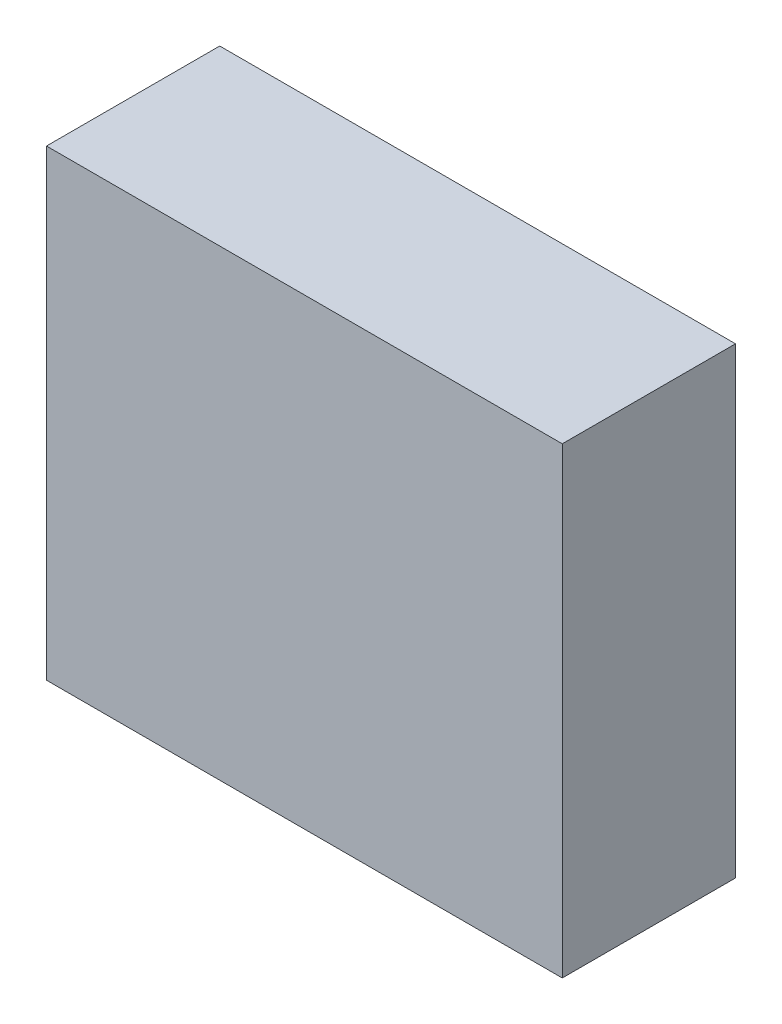
SolidWorks part; units mm, degrees
ref_plane "Front Plane" through (0, 0, 0) normal (0, 0, 1) x (1, 0, 0)
ref_plane "Top Plane" through (0, 0, 0) normal (0, 1, 0) x (1, 0, 0)
ref_plane "Right Plane" through (0, 0, 0) normal (1, 0, 0) x (0, 0, -1)
sketch "Sketch1" plane through (0, 0, 0) normal (0, 0, 1) x (1, 0, 0)
  line L0 (-1.4888, 1.4888) -> (1.4888, 1.4888)
  line L1 (1.4888, 1.4888) -> (1.4888, -1.182)
  line L2 (1.4888, -1.182) -> (-1.4888, -1.182)
  line L3 (-1.4888, -1.182) -> (-1.4888, 1.4888)
extrude "Component_Outline" add sketch "Sketch1" along normal blind 1 separate body
sketch3d "3DSketch1"
  line L0 (0, 0, 0) -> (1, 0, 0)
  line L1 (0, 0, 0) -> (0, 1, 0)
  line L2 (0, 0, 0) -> (0, 0, 1)
  point P0 (0, 0, 0)
